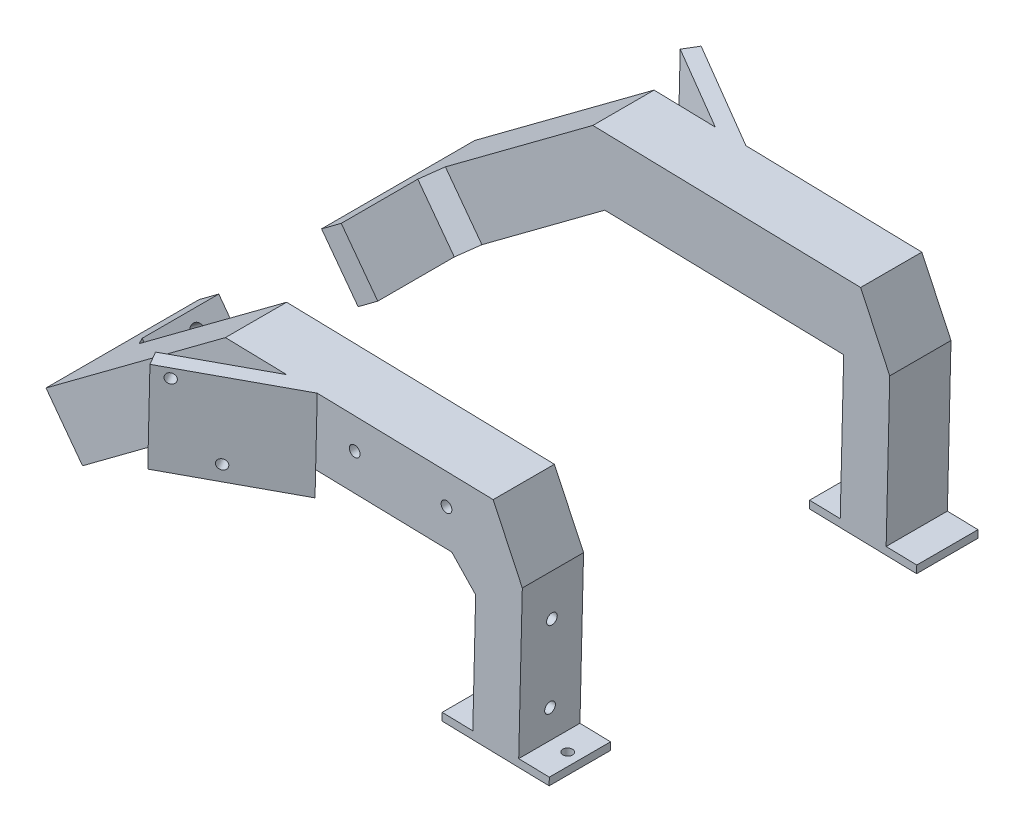
SolidWorks part; units mm, degrees
ref_plane "前视基准面" through (0, 0, 0) normal (0, 0, 1) x (1, 0, 0)
ref_plane "上视基准面" through (0, 0, 0) normal (0, 1, 0) x (1, 0, 0)
ref_plane "右视基准面" through (0, 0, 0) normal (1, 0, 0) x (0, 0, -1)
other "Configuration Table"
sketch "草图1" plane through (0, 0, 0) normal (0, 0, 1) x (1, 0, 0)
  line L0 (-24.7284, 34.0937) -> (-83.319, -9.4509)
  line L1 (-24.7284, 34.0937) -> (72.7186, 31.7458)
  line L3 (-20.8244, 12.0764) -> (72.1907, 9.8353)
  line L4 (72.7186, 31.7458) -> (72.1907, 9.8353)
  line L5 (49.8772, -39.0888) -> (103.8616, -40.3895) construction
  line L7 (-83.319, -9.4509) -> (-71.389, -25.5032)
  line L8 (-71.389, -25.5032) -> (-20.8244, 12.0764)
  line L11 (-60.0908, -36.4392) -> (39.8801, -38.848) construction
  point P0 (0, 0)
  dimension "D1" = 155
  dimension "D2" = 142
  dimension "D3" = 20
  dimension "D4" = 73
  dimension "D5" = 63
extrude "凸台-拉伸1" add sketch "草图1" along normal blind 20
sketch "草图2" plane through (0, 0, 0) normal (0, 0, -1) x (-1, 0, 0)
  line L0 (71.389, -25.5032) -> (83.319, -9.4509)
  line L1 (83.319, -9.4509) -> (76.8981, -4.6789)
  line L2 (24.7284, 34.0937) -> (83.319, -9.4509) construction
  line L3 (76.8981, -4.6789) -> (64.9681, -20.7312)
  line L4 (71.389, -25.5032) -> (20.8244, 12.0764) construction
  line L5 (64.9681, -20.7312) -> (71.389, -25.5032)
  dimension "D1" = 8
extrude "凸台-拉伸2" add sketch "草图2" along normal blind 30
sketch "草图3" plane through (-25.1214, 33.8016, 0) normal (-0.5965, 0.8026, 0) x (0.8026, 0.5965, 0)
  line L0 (-64.5103, 5) -> (-59.5103, 0)
  line L1 (-64.5103, 30) -> (-64.5103, 0) construction
  line L2 (0.4897, 0) -> (-64.5103, 0) construction
  line L3 (-59.5103, 0) -> (-64.5103, 0)
  line L4 (-64.5103, 0) -> (-64.5103, 5)
  dimension "D1" = 5
  dimension "D2" = 5
extrude "凸台-拉伸3" add sketch "草图3" along direction (-0.5965, 0.8026, 0) on the side against the normal up to surface (20 mm away)
sketch "草图4" plane through (0.2787, 11.568, 0) normal (-0.0241, -0.9997, 0) x (0.9997, -0.0241, 0)
  line L0 (-21.1093, 0) -> (71.9328, 0) construction
  line L1 (71.9328, 20) -> (56.9328, 20)
  line L2 (71.9328, 20) -> (71.9328, 0)
  line L3 (71.9328, 0) -> (56.9328, 0)
  line L4 (56.9328, 20) -> (56.9328, 0)
  line L5 (-21.1093, 20) -> (71.9328, 20) construction
  line L6 (71.9328, 20) -> (71.9328, 0) construction
  dimension "D1" = 15
extrude "凸台-拉伸4" add sketch "草图4" along normal up to surface (49.4474 mm away)
sketch "草图5" plane through (0, 0, 20) normal (0, 0, 1) x (1, 0, 0)
  line L0 (46.0069, -38.9956) -> (46.0671, -36.4963)
  line L1 (-60.0908, -36.4392) -> (39.8801, -38.848) construction
  line L2 (46.0671, -36.4963) -> (81.0569, -37.3394)
  line L3 (81.0569, -37.3394) -> (80.9967, -39.8386)
  line L4 (49.8772, -39.0888) -> (103.8616, -40.3895) construction
  line L5 (80.9967, -39.8386) -> (46.0069, -38.9956)
  line L8 (70.9996, -39.5978) -> (72.7186, 31.7458) construction
  line L9 (56.004, -39.2365) -> (57.195, 10.1966) construction
  dimension "D1" = 2.5
  dimension "D2" = 10
  dimension "D3" = 10
extrude "凸台-拉伸5" add sketch "草图5" against normal up to surface (20 mm away) up to face at (9.6905, -1.2708, 0)
sketch "草图6" plane through (0, 0, 20) normal (0, 0, 1) x (1, 0, 0)
  line L0 (62.7186, 31.9867) -> (72.2367, 11.7458)
  line L1 (72.7186, 31.7458) -> (-24.7284, 34.0937) construction
  line L2 (71.0598, -37.0985) -> (72.7186, 31.7458) construction
  line L3 (72.2367, 11.7458) -> (72.7186, 31.7458)
  line L4 (72.7186, 31.7458) -> (62.7186, 31.9867)
  dimension "D1" = 10
  dimension "D2" = 20
extrude "切除-拉伸1" cut sketch "草图6" against normal blind 30
sketch "草图7" plane through (0.8066, 33.4784, 0) normal (0.0241, 0.9997, 0) x (0.9997, -0.0241, 0)
  line L0 (-5.5424, -20) -> (-32.6834, -35.6699)
  line L1 (-32.6834, -35.6699) -> (-30.1834, -40)
  line L2 (-30.1834, -40) -> (4.4576, -20)
  line L3 (61.9299, -20) -> (-25.5424, -20) construction
  line L4 (4.4576, -20) -> (-5.5424, -20)
  line L6 (-25.5424, -20) -> (-25.5424, 0) construction
  dimension "D1" = 10
  dimension "D2" = 5
  dimension "D3" = 40
  dimension "D4" = 30
extrude "凸台-拉伸6" add sketch "草图7" against normal blind 30
ref_plane "基准面2" through (0, 0, -50) normal (0, 0, -1) x (-1, 0, 0)
mirror "镜向4" about plane through (0, 0, -50) normal (0, 0, -1) of bodies 112
other "保存实体2"
sketch "草图8" plane through (0, 0, 20) normal (0, 0, 1) x (1, 0, 0)
  line L0 (49.195, 10.3894) -> (57.0023, 2.1966)
  line L1 (4.735, 11.4606) -> (57.195, 10.1966) construction
  line L2 (56.0642, -36.7372) -> (57.195, 10.1966) construction
  line L3 (57.0023, 2.1966) -> (57.195, 10.1966)
  line L4 (57.195, 10.1966) -> (49.195, 10.3894)
  dimension "D1" = 8
  dimension "D2" = 8
extrude "凸台-拉伸7" add sketch "草图8" along direction (0, 0, 1) on the side against the normal up to surface (20 mm away)
sketch "草图9" plane through (-0.8521, -35.3658, 0) normal (0.0241, 0.9997, 0) x (0.9997, -0.0241, 0)
  line L0 (71.9328, 0) -> (81.9328, 0) construction
  line L1 (81.9328, 0) -> (81.9328, -20) construction
  line L2 (46.9328, 0) -> (46.9328, -20) construction
  line L3 (56.9328, -20) -> (46.9328, -20) construction
  circle A0 centre (77.9328, -10) radius 1.6
  circle A1 centre (50.9328, -10) radius 1.6
  dimension "D3" = 3.2
  dimension "D5" = 3.2
  dimension "D1" = 10
  dimension "D2" = 4
  dimension "D4" = 4
  dimension "D6" = 10
extrude "切除-拉伸2" cut sketch "草图9" against normal blind 10
sketch "草图10" plane through (-51.7767, -38.4805, 0) normal (0.8026, 0.5965, 0) x (0, 0, -1)
  line L0 (30, 42.1145) -> (5, 42.1145) construction
  line L1 (30, 42.1145) -> (30, 22.1145) construction
  line L2 (30, 22.1145) -> (5, 22.1145) construction
  circle A0 centre (20, 37.1145) radius 2.1
  circle A1 centre (20, 27.1145) radius 2.1
  dimension "D5" = 4.2
  dimension "D6" = 4.2
  dimension "D1" = 5
  dimension "D2" = 10
  dimension "D3" = 10
  dimension "D4" = 5
extrude "切除-拉伸3" cut sketch "草图10" against normal blind 10
sketch "草图11" plane through (56.9163, -1.3714, 0) normal (-0.9997, 0.0241, 0) x (0, 0, 1)
  line L0 (0, 3.569) -> (20, 3.569) construction
  line L1 (0, -35.3761) -> (0, 3.569) construction
  circle A0 centre (10, -0.431) radius 1.75
  circle A1 centre (10, -25.831) radius 1.75
  dimension "D2" = 3.5
  dimension "D6" = 3.5
  dimension "D1" = 4
  dimension "D3" = 10
  dimension "D4" = 25.4
  dimension "D5" = 10
extrude "切除-拉伸4" cut sketch "草图11" against normal through all
sketch "草图12" plane through (9.7718, -0.2354, 16.9302) normal (0.4999, -0.012, 0.866) x (0.8661, 0.007, -0.4998)
  line L0 (-40.2758, 31.6205) -> (-28.1925, 9.2788)
  line L1 (-45.1904, 34.7584) -> (-5.2059, 33.646) construction
  line L2 (-46.0248, 4.77) -> (-45.1904, 34.7584) construction
  circle A0 centre (-40.2758, 31.6205) radius 1.6
  circle A1 centre (-28.1925, 9.2788) radius 1.6
  dimension "D2" = 3.2
  dimension "D3" = 3.2
  dimension "D1" = 3
  dimension "D4" = 25.4
  dimension "D5" = 30
  dimension "D6" = 5
extrude "切除-拉伸5" cut sketch "草图12" against normal blind 10
sketch "草图13" plane through (0, 0, 0) normal (0, 0, -1) x (-1, 0, 0)
  line L0 (-47.485, 22.3509) -> (-17.4937, 23.0735)
  line L1 (-62.7186, 31.9867) -> (24.7284, 34.0937) construction
  line L2 (-71.0598, -37.0985) -> (-72.2367, 11.7458) construction
  circle A0 centre (-47.485, 22.3509) radius 1.75
  circle A1 centre (-17.4937, 23.0735) radius 1.75
  dimension "D3" = 3.5
  dimension "D4" = 3.5
  dimension "D1" = 10
  dimension "D2" = 30
  dimension "D5" = 25
extrude "切除-拉伸7" cut sketch "草图13" against normal blind 20
